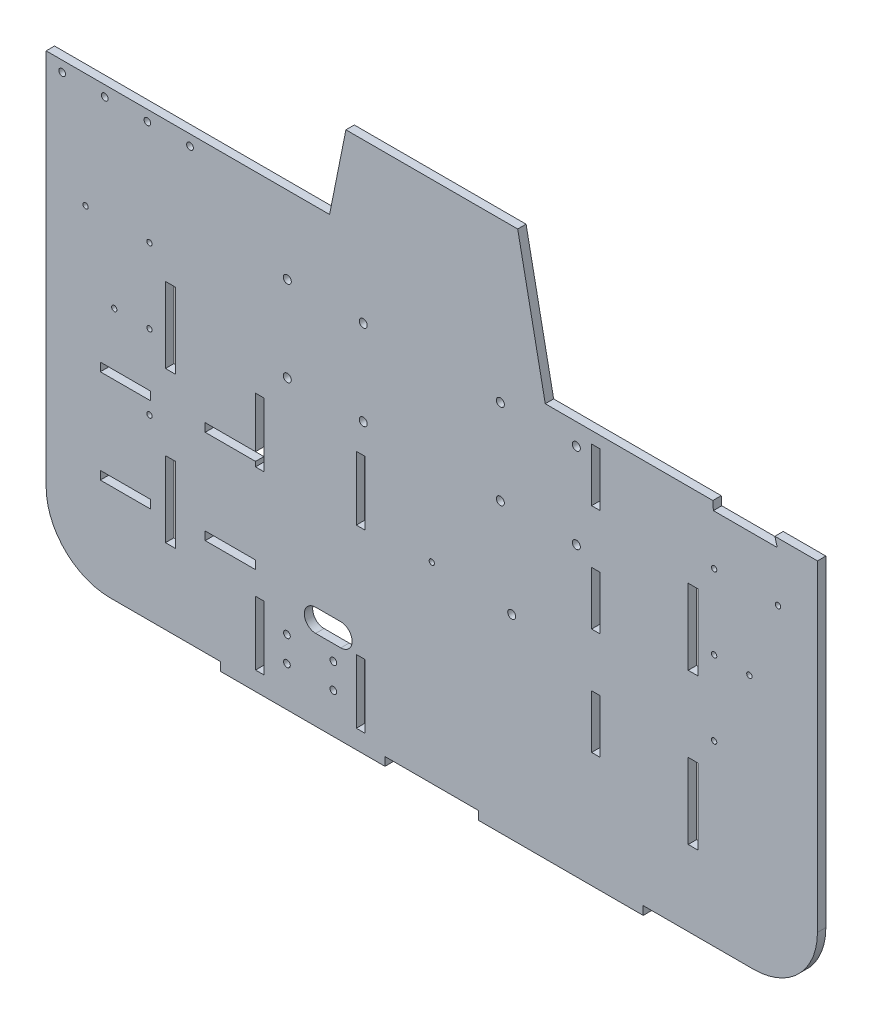
SolidWorks part; units mm, degrees
material "Gillfab4009"
ref_plane "Front Plane" through (0, 0, 0) normal (0, 0, 1) x (1, 0, 0)
ref_plane "Top Plane" through (0, 0, 0) normal (0, 1, 0) x (1, 0, 0)
ref_plane "Right Plane" through (0, 0, 0) normal (1, 0, 0) x (0, 0, -1)
sketch "Sketch2" plane through (0, 0, 0) normal (0, 0, 1) x (1, 0, 0)
  line L0 (-408.9218, 152.7574) -> (-459.7218, 152.7574)
  line L1 (335.0225, 152.7574) -> (135.2505, 152.7574)
  line L2 (-135.2505, 152.7574) -> (-332.5791, 152.7574)
  line L3 (-102.3945, 316.7286) -> (-135.2505, 152.7574)
  line L4 (102.3945, 316.7286) -> (-102.3945, 316.7286)
  line L6 (-459.7218, 152.7574) -> (-459.7218, -230.7826)
  line L7 (459.7218, 152.7574) -> (408.9218, 152.7574)
  line L8 (-303.52, -306.9826) -> (-383.5218, -306.9826)
  line L9 (-252, -317.1426) -> (-55.8292, -317.1426)
  line L11 (411.8447, 142.5974) -> (408.9218, 152.7574)
  line L12 (335.6447, 142.5974) -> (411.8447, 142.5974)
  line L13 (335.0225, 152.7574) -> (335.6447, 142.5974)
  line L14 (-408.9218, 142.5974) -> (-332.7218, 142.5974)
  line L15 (-408.9218, 152.7574) -> (-408.9218, 142.5974)
  line L16 (-332.7218, 142.5974) -> (-332.5791, 152.7574)
  line L17 (305.6323, -37.2346) -> (317.4824, -37.2346)
  line L18 (305.6323, 52.6814) -> (305.6323, -37.2346)
  line L19 (317.4824, 52.6814) -> (305.6323, 52.6814)
  line L20 (317.4824, -37.2346) -> (317.4824, 52.6814)
  line L21 (305.6323, -217.0666) -> (317.4824, -217.0666)
  line L22 (317.4824, -217.0666) -> (317.4824, -127.1506)
  line L23 (317.4824, -127.1506) -> (305.6323, -127.1506)
  line L24 (305.6323, -127.1506) -> (305.6323, -217.0666)
  line L25 (252, -307.3966) -> (202.6964, -307.3966) construction
  line L26 (252, -317.1426) -> (252, -307.3966) construction
  line L27 (0, 316.7286) -> (0, 0) construction
  line L28 (0, 0) -> (0, -307.6709) construction
  line L39 (303.52, -306.9826) -> (383.5218, -306.9826)
  line L44 (-190.5, 75.1277) -> (-190.5, 11.4601) construction
  line L45 (-190.5, -52.225) -> (-190.5, -115.91) construction
  line L46 (-190.5, -179.5951) -> (-190.5, -243.2802) construction
  line L47 (190.5, 75.1277) -> (190.5, 14.3511) construction
  line L48 (190.5, -307.3966) -> (190.5, -243.6941) construction
  line L49 (190.5, 14.3511) -> (190.5, -115.91) construction
  line L52 (190.5, -115.91) -> (190.5, -243.6941) construction
  line L53 (459.7218, 152.7574) -> (459.7218, 465.1616) construction
  line L55 (-335.16, -69.447) -> (-335.16, -79.447)
  line L56 (459.7218, 152.7574) -> (459.7218, -230.7826)
  line L57 (-270.16, -79.447) -> (-210.16, -79.447)
  line L58 (-270.16, -79.447) -> (-270.16, -69.447)
  line L59 (-335.16, -69.447) -> (-395.16, -69.447)
  line L60 (-395.16, -79.447) -> (-210.16, -79.447)
  line L61 (-210.16, -79.447) -> (-210.16, -69.447)
  line L62 (102.3945, 316.7286) -> (135.2505, 152.7574)
  line L63 (-210.16, -69.447) -> (-395.16, -69.447)
  line L64 (-395.16, -69.447) -> (-395.16, -79.447)
  line L65 (-395.16, -79.447) -> (-335.16, -79.447)
  line L67 (-210.16, -69.447) -> (-270.16, -69.447)
  line L68 (-395.16, -69.447) -> (-395.16, -79.447)
  line L69 (-210.16, -191.2542) -> (-395.16, -191.2542) construction
  line L70 (0, -307.6709) -> (0, -629.2246) construction
  line L71 (-210.16, -181.2542) -> (-395.16, -181.2542) construction
  line L72 (-335.16, -191.2542) -> (-335.16, -181.2542) construction
  line L73 (-270.16, -191.2542) -> (-270.16, -181.2542) construction
  line L75 (202.6964, -243.6941) -> (190.5, -243.6941) construction
  line L76 (202.6964, -243.6941) -> (202.6964, -307.3966) construction
  line L79 (200.66, -179.5951) -> (190.5, -179.5951)
  line L80 (190.5, -179.5951) -> (190.5, -115.91)
  line L81 (200.66, -115.91) -> (190.5, -115.91)
  line L82 (200.66, -115.91) -> (200.66, -179.5951)
  line L83 (190.5, -52.225) -> (190.5, 11.4601)
  line L84 (200.66, 11.4601) -> (190.5, 11.4601)
  line L85 (200.66, 11.4601) -> (200.66, -52.225)
  line L86 (200.66, -52.225) -> (190.5, -52.225)
  line L87 (200.66, 138.8128) -> (190.5, 138.8128)
  line L88 (190.5, 75.1277) -> (190.5, 138.8128)
  line L89 (200.66, 75.1277) -> (190.5, 75.1277)
  line L90 (200.66, 138.8128) -> (200.66, 75.1277)
  line L103 (-210.16, -191.4142) -> (-210.16, -294.8827) construction
  line L105 (-210.16, -191.2542) -> (-210.16, -181.2542) construction
  line L106 (-210.16, -79.447) -> (-210.16, -181.2542) construction
  line L107 (-200, -191.4142) -> (-200, -294.8827) construction
  line L108 (-200, -294.8827) -> (-210.16, -294.8827) construction
  line L109 (-200, -218.6827) -> (-210.16, -218.6827) construction
  line L110 (-200, -85.1624) -> (-210.16, -85.1624) construction
  line L111 (-200, -85.1624) -> (-210.16, -85.1624)
  line L112 (-200, -218.6827) -> (-210.16, -218.6827)
  line L113 (-200, -294.8827) -> (-210.16, -294.8827)
  line L114 (-200, -218.6827) -> (-200, -294.8827)
  line L115 (-210.16, -79.447) -> (-210.16, -85.1624)
  line L116 (-210.16, -191.2542) -> (-210.16, -181.2542)
  line L117 (-210.16, -218.6827) -> (-210.16, -294.8827)
  line L118 (-270.16, -191.2542) -> (-270.16, -181.2542)
  line L119 (-335.16, -191.2542) -> (-335.16, -181.2542)
  line L120 (-210.16, -181.2542) -> (-270.16, -181.2542)
  line L121 (-210.16, -191.2542) -> (-270.16, -191.2542)
  line L122 (-395.16, -181.2542) -> (-395.16, -191.2542)
  line L123 (-335.16, -191.2542) -> (-395.16, -191.2542)
  line L124 (-335.16, -181.2542) -> (-395.16, -181.2542)
  line L125 (-210.16, -69.447) -> (-210.16, -8.9624)
  line L126 (-210.16, -8.9624) -> (-200, -8.9624)
  line L127 (-200, -8.9624) -> (-200, -85.1624)
  line L128 (305.6323, -37.2346) -> (305.6323, -217.0666) construction
  line L129 (317.4824, -37.2346) -> (317.4824, -217.0666) construction
  line L130 (-305.6323, -217.0666) -> (-317.4824, -217.0666)
  line L131 (-305.6323, -127.1506) -> (-305.6323, -217.0666)
  line L132 (-90, -218.6827) -> (-90, -294.8827)
  line L133 (-79.84, -218.6827) -> (-90, -218.6827)
  line L134 (-79.84, -294.8827) -> (-79.84, -218.6827)
  line L135 (-90, -294.8827) -> (-79.84, -294.8827)
  line L136 (-90, -218.6827) -> (-90, -294.8827)
  line L137 (-79.84, -218.6827) -> (-90, -218.6827)
  line L138 (-79.84, -294.8827) -> (-79.84, -218.6827)
  line L139 (-90, -294.8827) -> (-79.84, -294.8827)
  line L140 (-90, -8.9624) -> (-90, -85.1624)
  line L141 (-79.84, -8.9624) -> (-90, -8.9624)
  line L142 (-79.84, -85.1624) -> (-79.84, -8.9624)
  line L143 (-90, -85.1624) -> (-79.84, -85.1624)
  line L144 (-90, -8.9624) -> (-90, -85.1624)
  line L145 (-79.84, -8.9624) -> (-90, -8.9624)
  line L146 (-79.84, -85.1624) -> (-79.84, -8.9624)
  line L147 (-90, -85.1624) -> (-79.84, -85.1624)
  line L148 (-317.4824, -127.1506) -> (-305.6323, -127.1506)
  line L149 (-317.4824, -217.0666) -> (-317.4824, -127.1506)
  line L150 (-305.6323, -37.2346) -> (-317.4824, -37.2346)
  line L151 (-317.4824, -37.2346) -> (-317.4824, 52.6814)
  line L152 (-317.4824, 52.6814) -> (-305.6323, 52.6814)
  line L153 (-305.6323, 52.6814) -> (-305.6323, -37.2346)
  line L154 (-183, -317.1426) -> (-183, -226.646) construction
  line L155 (-183, -304.4426) -> (-107.07, -304.4426) construction
  line L156 (-108.5, -207.6709) -> (-138.5, -207.6709) construction
  line L157 (-108.5, -221.1709) -> (-138.5, -221.1709)
  line L158 (-108.5, -194.1709) -> (-138.5, -194.1709)
  line L159 (-90, -191.4142) -> (-90, -294.8827) construction
  line L160 (-145.035, -304.4426) -> (-145.035, -269.4426) construction
  line L161 (-172.69, -269.4426) -> (-117.38, -269.4426) construction
  line L162 (-145.035, -239.4426) -> (-145.035, -269.4426) construction
  line L163 (-172.69, -239.4426) -> (-117.38, -239.4426) construction
  line L164 (-55.8292, -306.9826) -> (55.8292, -306.9826) construction
  line L165 (-55.8292, -306.9826) -> (55.8292, -306.9826)
  line L166 (-55.8292, -306.9826) -> (-55.8292, -317.1426) construction
  line L167 (55.8292, -306.9826) -> (55.8292, -317.1426) construction
  line L168 (-55.8292, -306.9826) -> (-55.8292, -317.1426)
  line L169 (55.8292, -306.9826) -> (55.8292, -317.1426)
  line L170 (303.52, -306.9826) -> (252, -306.9826) construction
  line L171 (-303.52, -306.9826) -> (-252, -306.9826) construction
  line L172 (-252, -306.9826) -> (-252, -317.1426) construction
  line L173 (-252, -306.9826) -> (-252, -317.1426)
  line L174 (-303.52, -306.9826) -> (-252, -306.9826)
  line L175 (303.52, -306.9826) -> (252, -306.9826)
  line L176 (252, -306.9826) -> (252, -317.1426) construction
  line L177 (252, -306.9826) -> (252, -317.1426)
  line L178 (55.8292, -317.1426) -> (252, -317.1426)
  line L179 (-459.7218, 152.7574) -> (-459.7218, 194.1858)
  line L180 (-459.7218, 194.1858) -> (-459.7218, 219.5858)
  line L181 (-459.7218, 219.5858) -> (-121.8597, 219.5858)
  arc A0 (-383.5218, -306.9826) -> (-459.7218, -230.7826) centre (-383.5218, -230.7826) cw
  arc A2 (383.5218, -306.9826) -> (459.7218, -230.7826) centre (383.5218, -230.7826) ccw
  circle A6 centre (336.5503, -94.6874) radius 3.175
  circle A7 centre (378.5738, -5.7874) radius 3.175
  circle A8 centre (336.5503, -5.7874) radius 3.175
  circle A9 centre (336.5503, 83.1126) radius 3.175
  circle A10 centre (412.7503, 83.1126) radius 3.175
  circle A11 centre (-412.7503, 83.1126) radius 3.175
  circle A12 centre (-336.5503, 83.1126) radius 3.175
  circle A13 centre (-336.5503, -5.7874) radius 3.175
  circle A14 centre (-378.5738, -5.7874) radius 3.175
  circle A15 centre (-336.5503, -94.6874) radius 3.175
  circle A18 centre (172.2755, 127.3574) radius 4.7625
  circle A19 centre (172.2755, 25.7574) radius 4.7625
  circle A20 centre (81.7245, 25.7574) radius 4.7625
  circle A21 centre (81.7245, 127.3574) radius 4.7625
  circle A22 centre (-81.7245, 25.7574) radius 4.7625
  circle A23 centre (-81.7245, 127.3574) radius 4.7625
  circle A24 centre (-172.2755, 127.3574) radius 4.7625
  circle A25 centre (-172.2755, 25.7574) radius 4.7625
  circle A26 centre (0, -78.3826) radius 3.175
  circle A28 centre (95.25, -84.7326) radius 4.7625
  arc A29 (-108.5, -221.1709) -> (-108.5, -194.1709) centre (-108.5, -207.6709) ccw
  arc A30 (-138.5, -194.1709) -> (-138.5, -221.1709) centre (-138.5, -207.6709) ccw
  circle A31 centre (-172.69, -239.4426) radius 4
  circle A32 centre (-117.38, -239.4426) radius 4
  circle A33 centre (-117.38, -269.4426) radius 4
  circle A34 centre (-172.69, -269.4426) radius 4
  circle A35 centre (-440.6718, 206.8858) radius 4
  circle A36 centre (-389.8718, 206.8858) radius 4
  circle A37 centre (-339.0718, 206.8858) radius 4
  circle A38 centre (-288.2718, 206.8858) radius 4
  point P59 (-123.5, -207.6709)
  point P74 (-145.035, -269.4426)
  point P128 (-95, -207.6709)
  point P173 (-145.035, -239.4426)
  dimension "D1" = 76.2
  dimension "D8" = 76.2
  dimension "D21" = 27
  dimension "D22" = 30
  dimension "D33" = 8
  dimension "D34" = 90
  dimension "D37" = 8
  dimension "D38" = 12.7
  dimension "D39" = 19.05
  dimension "D41" = 50.8
  dimension "D42" = 206.8858
  dimension "D3" = 919.4436
  dimension "D4" = 305.6323
  dimension "D5" = 183
  dimension "D6" = 12.7
  dimension "D7" = 152.7574
  dimension "D9" = 75.93
  dimension "D10" = 90
  dimension "D11" = 35
  dimension "D12" = 10.16
  dimension "D13" = 190.5
  dimension "D14" = 190.5
  dimension "D15" = 50.8
  dimension "D16" = 0
  dimension "D17" = 50.8
  dimension "D18" = 76.2
  dimension "D19" = 0
  dimension "D23" = 5
  dimension "D24" = 55.31
  dimension "D25" = 11.8501
  dimension "D26" = 52.6814
  dimension "D27" = 89.916
  dimension "D28" = 89.916
  dimension "D29" = 89.916
  dimension "D30" = 316.7286
  dimension "D31" = 55.31
  dimension "D32" = 30
  dimension "D35" = 25.4
  dimension "D36" = 41.4284
  dimension "D20" = 0
  dimension "D40" = 4
extrude "Boss-Extrude1" add sketch "Sketch2" against normal blind 10 contours L181 L180 L179 L0 L15 L14 L16 L2 L3 A38 A37 A36 A35 | L39 A2 L56 L7 L11 L12 L13 L1 L62 L4 L3 L2 L16 L14 L15 L0 L6 A0 L8 L174 L173 L9 L168 L165 L169 L178 L177 L175 A34 A33 A32 A31 A30 L158 A29 L157 A28 A26 A25 A24
